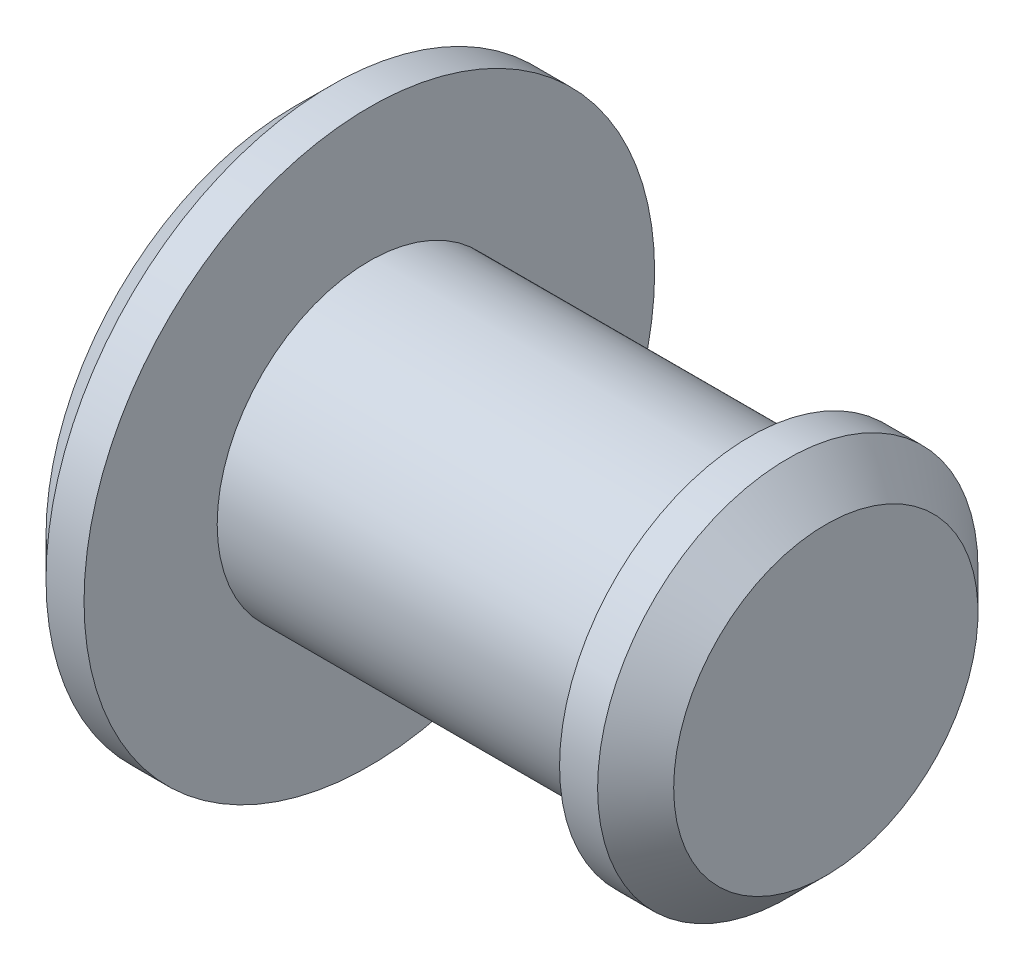
SolidWorks part; units mm, degrees
ref_plane "Piano frontale" through (0, 0, 0) normal (0, 0, 1) x (1, 0, 0)
ref_plane "Piano superiore" through (0, 0, 0) normal (0, 1, 0) x (1, 0, 0)
ref_plane "Piano destro" through (0, 0, 0) normal (1, 0, 0) x (0, 0, -1)
sketch "Schizzo1" plane through (0, 0, 0) normal (0, 0, 1) x (1, 0, 0)
  line L0 (-5.1735, 0) -> (9.9894, 0) construction
  line L1 (0, 0) -> (0, 3.75)
  line L2 (0, 3.75) -> (1, 3.75)
  line L3 (1, 3.75) -> (1, 2)
  line L4 (1, 2) -> (6, 2)
  line L5 (6, 2) -> (6, 2.5)
  line L6 (6, 2.5) -> (7, 2.5)
  line L7 (7, 2.5) -> (7, 0)
  line L8 (7, 0) -> (0, 0)
  point P5 (0, 0)
  point P12 (9.9894, 0)
  dimension "D1" = 7.5
  dimension "D2" = 1
  dimension "D3" = 4
  dimension "D4" = 5
  dimension "D5" = 1
  dimension "D6" = 7
revolve "Rivoluzione1" add sketch "Schizzo1" angle 360 about L0
chamfer "Smusso1" distance 0.5 angle 45 2 edges at (7, 0, 2.5) (0, 0, 3.75)
